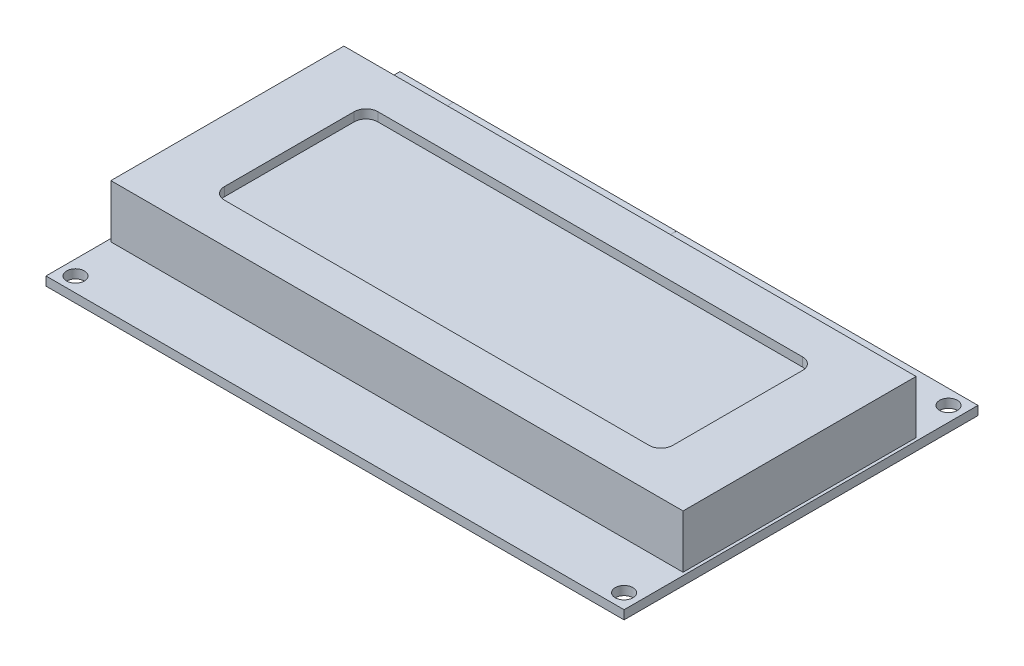
SolidWorks part; units mm, degrees
ref_plane "Front Plane" through (0, 0, 0) normal (0, 0, 1) x (1, 0, 0)
ref_plane "Top Plane" through (0, 0, 0) normal (0, 1, 0) x (1, 0, 0)
ref_plane "Right Plane" through (0, 0, 0) normal (1, 0, 0) x (0, 0, -1)
sketch "Sketch1" plane through (0, 0, 0) normal (0, 1, 0) x (1, 0, 0)
  line L0 (49, -30) -> (-49, 30) construction
  line L1 (-49, 30) -> (49, 30)
  line L2 (-49, 30) -> (-49, -30)
  line L3 (-49, -30) -> (49, -30)
  line L4 (49, 30) -> (49, -30)
  dimension "D1" = 98
  dimension "D2" = 60
extrude "Boss-Extrude1" add sketch "Sketch1" along normal blind 1.5
sketch "Sketch2" plane through (0, 1.5, 0) normal (0, 1, 0) x (1, 0, 0)
  line L0 (-49, 30) -> (-49, -30) construction
  line L1 (-48.5, 20) -> (48.5, 20)
  line L2 (-48.5, 20) -> (-48.5, -19.5)
  line L3 (-48.5, -19.5) -> (48.5, -19.5)
  line L4 (48.5, 20) -> (48.5, -19.5)
  line L5 (49, -30) -> (49, 30) construction
  line L6 (49, 30) -> (-49, 30) construction
  line L7 (-49, -30) -> (49, -30) construction
  dimension "D1" = 0.5
  dimension "D2" = 0.5
  dimension "D3" = 10
  dimension "D4" = 10.5
extrude "Boss-Extrude2" add sketch "Sketch2" along normal blind 9
sketch "Sketch3" plane through (0, 10.5, 0) normal (0, 1, 0) x (1, 0, 0)
  line L0 (-48.5, 0.25) -> (-38, 0.25) construction
  line L1 (-36, 13.25) -> (36, 13.25)
  line L2 (-38, 11.25) -> (-38, -10.75)
  line L3 (-36, -12.75) -> (36, -12.75)
  line L4 (38, 11.25) -> (38, -10.75)
  line L5 (-48.5, 20) -> (-48.5, -19.5) construction
  line L6 (0, 13.25) -> (0, 0) construction
  arc A0 (36, 13.25) -> (38, 11.25) centre (36, 11.25) cw
  arc A1 (-38, -10.75) -> (-36, -12.75) centre (-36, -10.75) ccw
  arc A2 (36, -12.75) -> (38, -10.75) centre (36, -10.75) ccw
  arc A3 (-36, 13.25) -> (-38, 11.25) centre (-36, 11.25) ccw
  point P13 (38, 13.25)
  point P16 (-38, -12.75)
  point P21 (-38, 13.25)
  dimension "D3" = 2
  dimension "D1" = 76
  dimension "D2" = 26
extrude "Cut-Extrude1" cut sketch "Sketch3" against normal blind 1.5
sketch "Sketch4" plane through (0, 1.5, 0) normal (0, 1, 0) x (1, 0, 0)
  line L0 (-46.5, -27.5) -> (46.5, -27.5) construction
  line L1 (46.5, -27.5) -> (46.5, 27.5) construction
  line L2 (46.5, 27.5) -> (-46.5, 27.5) construction
  line L3 (-46.5, 27.5) -> (-46.5, -27.5) construction
  line L4 (-46.5, 27.5) -> (46.5, -27.5) construction
  circle A0 centre (-46.5, 27.5) radius 1.5
  circle A1 centre (46.5, 27.5) radius 1.5
  circle A2 centre (46.5, -27.5) radius 1.5
  circle A3 centre (-46.5, -27.5) radius 1.5
  dimension "D1" = 3
  dimension "D2" = 93
  dimension "D3" = 55
extrude "Cut-Extrude2" cut sketch "Sketch4" against normal up to next
sketch "Sketch5" plane through (0, 1.5, 0) normal (0, 1, 0) x (1, 0, 0)
  line L0 (49, 30) -> (-49, 30) construction
  line L1 (-39.9546, 30) -> (-2.1452, 30)
  line L2 (-39.9546, 30) -> (-39.9546, 25.4744)
  line L3 (-39.9546, 25.4744) -> (-2.1452, 25.4744)
  line L4 (-2.1452, 30) -> (-2.1452, 25.4744)
extrude "Boss-Extrude3" add sketch "Sketch5" along normal blind 0.01
